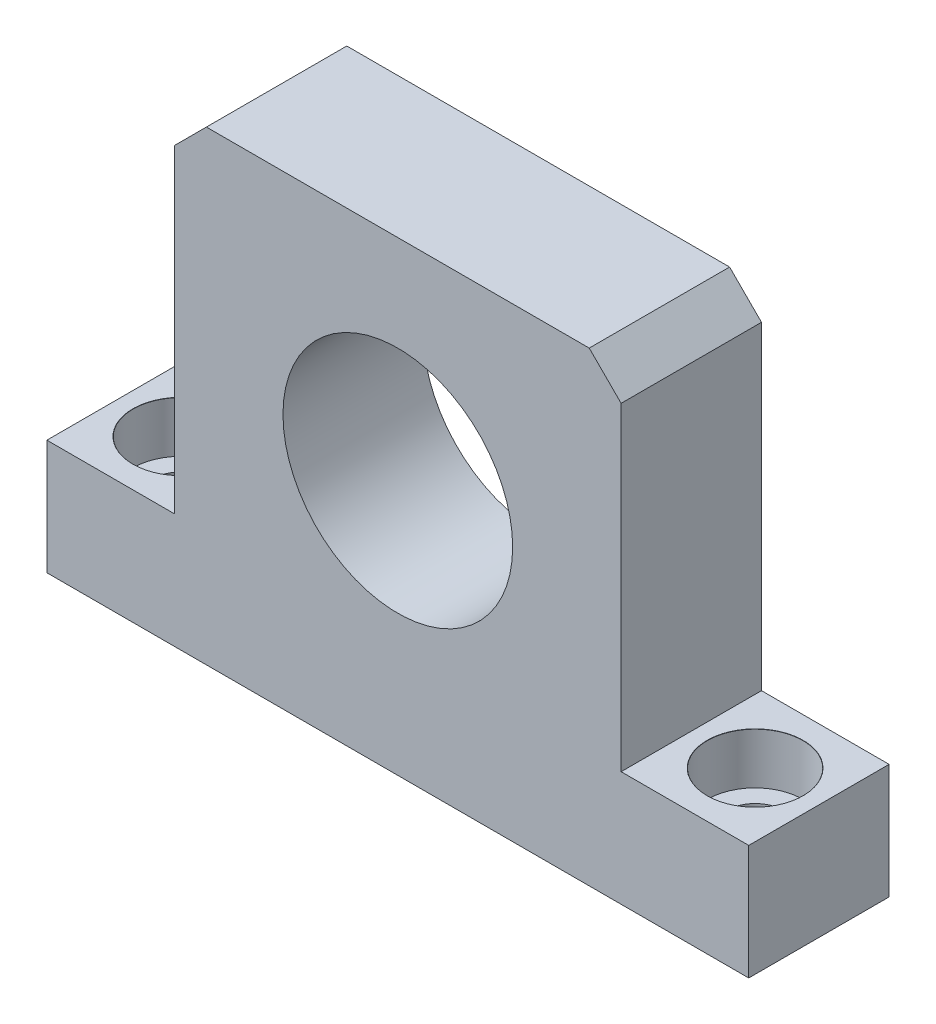
SolidWorks part; units mm, degrees
ref_plane "前视基准面" through (0, 0, 0) normal (0, 0, 1) x (1, 0, 0)
ref_plane "上视基准面" through (0, 0, 0) normal (0, 1, 0) x (1, 0, 0)
ref_plane "右视基准面" through (0, 0, 0) normal (1, 0, 0) x (0, 0, -1)
sketch "草图1" plane through (0, 0, 0) normal (0, 0, 1) x (1, 0, 0)
  line L0 (35, 18) -> (55, 18)
  line L1 (-55, 0) -> (55, 0)
  line L2 (-55, 0) -> (-55, 18)
  line L3 (-55, 18) -> (-35, 18)
  line L4 (55, 0) -> (55, 18)
  line L5 (-35, 68) -> (-30, 73)
  line L6 (-35, 18) -> (-35, 68)
  line L7 (-30, 73) -> (30, 73)
  line L8 (35, 18) -> (35, 68)
  line L9 (30, 73) -> (35, 68)
  line L10 (0, 73) -> (0, 0) construction
  circle A0 centre (0, 40) radius 18
  point P5 (35, 73)
  point P6 (-35, 73)
  point P10 (0, 0)
  point P30 (0, 73)
  dimension "D5" = 36
  dimension "D6" = 40
  dimension "D1" = 110
  dimension "D2" = 70
  dimension "D3" = 73
  dimension "D4" = 55
extrude "拉伸1" add sketch "草图1" along normal mid plane 22
hole_wizard "M8 六角凹头螺钉的柱形沉头孔1" positions "3D草图1" profile "草图2" counterbore size "M8" standard "ISO" end condition through all
sketch3d "3D草图1"
  point P2 (-45, 18, 0)
  point P4 (45, 18, 0)
sketch "草图2" plane through (-45, 18, 0) normal (1, 0, 0) x (0, 0, 1)
  line L0 (0, 0) -> (0, 18)
  line L1 (0, 18) -> (4.5, 18)
  line L3 (4.5, 18) -> (4.5, 8)
  line L4 (7.5, 8) -> (4.5, 8)
  line L5 (7.5, 8) -> (7.5, 0.025)
  line L6 (7.5, 0.025) -> (7.525, 0)
  line L7 (7.525, 0) -> (0, 0)
  line L8 (-7.5, 0.025) -> (-7.525, 0) construction
  line L11 (0, -6.35) -> (0, 107.95) construction
  dimension "通孔孔直径" = 9
  dimension "通孔孔深度" = 18
  dimension "柱形沉头孔直径" = 15
  dimension "柱形沉头孔深度" = 8
  dimension "近端锥形沉头孔直径" = 15.05
  dimension "近端锥形沉头孔角度" = 90
hole_wizard "M6 螺纹孔1" positions "草图4" profile "草图3" tap size "M6" standard "GB"
sketch "草图4" plane through (0, 0, -11) normal (0, 0, -1) x (-1, 0, 0)
  point P0 (16.6159, 25.383)
  point P1 (-16.6181, 25.383)
  point P3 (-23.5011, 42)
  point P5 (-16.6181, 58.617)
  point P7 (16.6159, 58.617)
  point P9 (23.4989, 42)
sketch "草图3" plane through (-16.6159, 25.383, -11) normal (1, 0, 0) x (0, 1, 0)
  line L0 (0, 0) -> (0, 16.5022)
  line L1 (0, 16.5022) -> (2.5, 15)
  line L2 (2.5, 15) -> (2.5, 0)
  line L5 (2.5, 0) -> (0, 0)
  line L10 (0, 16.5022) -> (-2.5, 15) construction
  line L11 (0, -6.35) -> (0, 107.95) construction
  dimension "螺纹孔钻头直径" = 5
  dimension "螺纹孔钻头深度" = 15
  dimension "导头角度" = 118
cosmetic thread "孔螺蚊线1" parameters "D1"=12, "D2"=6
cosmetic thread "孔螺蚊线2" parameters "D1"=12, "D2"=6
cosmetic thread "孔螺蚊线3" parameters "D1"=12, "D2"=6
cosmetic thread "孔螺蚊线4" parameters "D1"=12, "D2"=6
cosmetic thread "孔螺蚊线5" parameters "D1"=12, "D2"=6
cosmetic thread "孔螺蚊线6" parameters "D1"=12, "D2"=6
